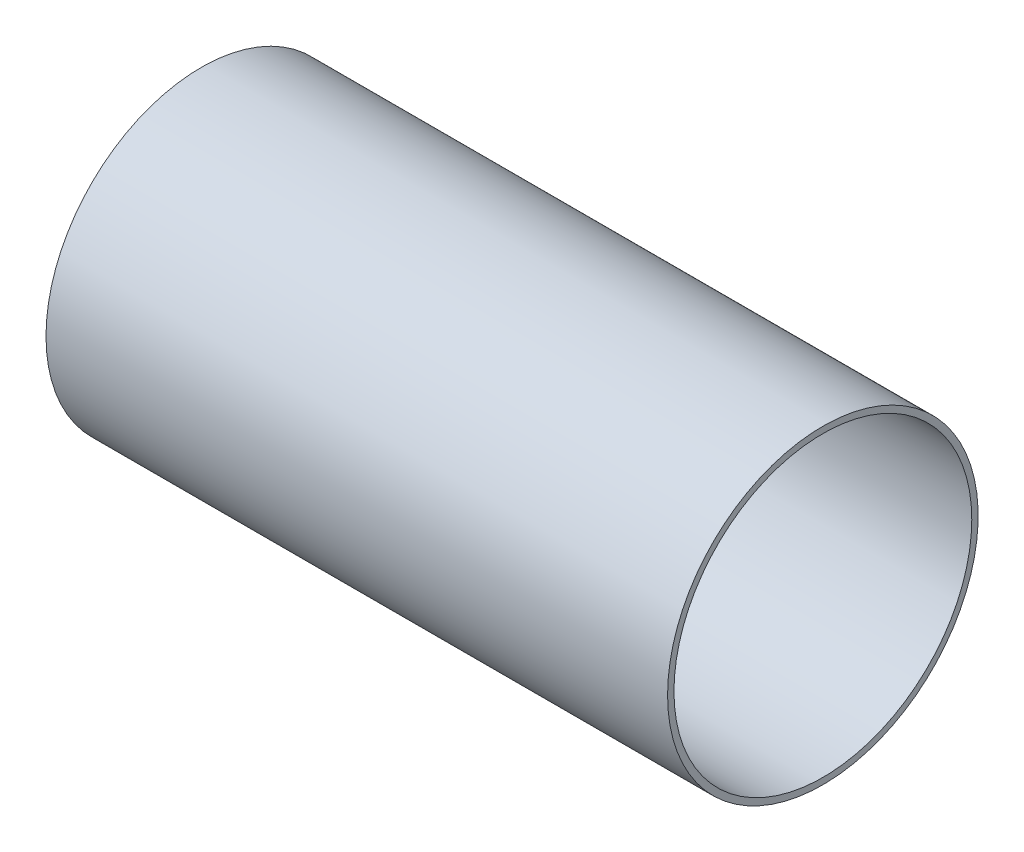
SolidWorks part; units mm, degrees
ref_plane "Front Plane" through (0, 0, 0) normal (1, 0, 0) x (0, 1, 0)
ref_plane "Top Plane" through (0, 0, 0) normal (0, 0, 1) x (0, 1, 0)
ref_plane "Right Plane" through (0, 0, 0) normal (0, 1, 0) x (-1, 0, 0)
sketch "Sketch1" plane through (0, 0, 0) normal (1, 0, 0) x (0, 1, 0)
  circle A0 centre (0, 0) radius 36.5125
  circle A1 centre (0, 0) radius 38.0746
  point P5 (0, 0)
  point P6 (0, -0.4074)
  point P7 (0.0109, 0)
  dimension "D1" = 76.1492
  dimension "D2" = 73.025
extrude "Boss-Extrude1" add sketch "Sketch1" along normal blind 152.4
